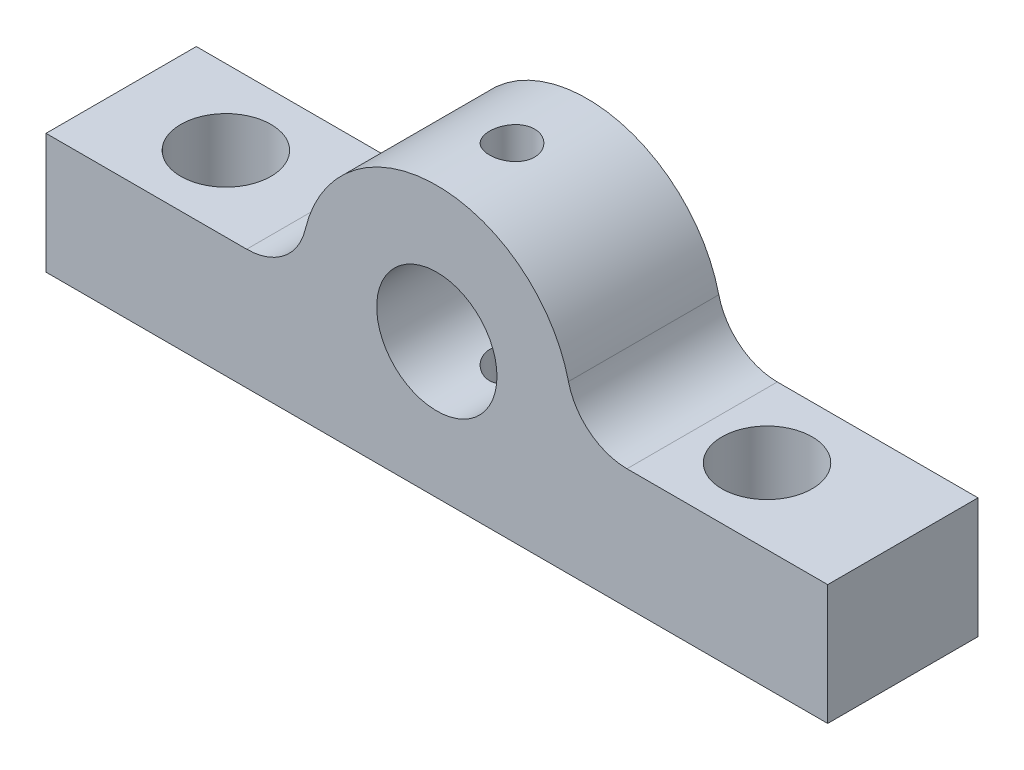
SolidWorks part; units mm, degrees
ref_plane "Front Plane" through (0, 0, 0) normal (0, 0, 1) x (1, 0, 0)
ref_plane "Top Plane" through (0, 0, 0) normal (0, 1, 0) x (1, 0, 0)
ref_plane "Right Plane" through (0, 0, 0) normal (1, 0, 0) x (0, 0, -1)
sketch "Sketch1" plane through (0, 0, 0) normal (0, 0, 1) x (1, 0, 0)
  line L0 (0, -36.257) -> (0, 59.0013) construction
  line L1 (13, 0) -> (-13, 0)
  line L2 (-13, 0) -> (-13, 4)
  line L3 (-13, 4) -> (-6.3246, 4)
  line L4 (13, 4) -> (13, 0)
  line L5 (0, 0) -> (0, 4.5)
  line L6 (6.3246, 4) -> (13, 4)
  arc A0 (4.3785, 5.5385) -> (-4.3785, 5.5385) centre (0, 4.5) ccw
  circle A1 centre (0, 4.5) radius 2
  arc A2 (-4.3785, 5.5385) -> (-6.3246, 4) centre (-6.3246, 6) cw
  arc A3 (6.3246, 4) -> (4.3785, 5.5385) centre (6.3246, 6) cw
  point P6 (0, 0)
  point P17 (4.4721, 4)
  dimension "D1" = 2
  dimension "D2" = 2
extrude "Boss-Extrude1" add sketch "Sketch1" along normal blind 5 contours A1 L0 A0 A2 L3 L2 L1 L5 | L0 A1 L5 L1 L4 L6 A3 A0
sketch "Sketch2" plane through (0, 4, 0) normal (0, 1, 0) x (1, 0, 0)
  line L0 (-0.5173, -2.5) -> (-9.5173, -2.5)
  line L1 (-0.5173, -2.5) -> (8.4827, -2.5)
  circle A0 centre (-9.5173, -2.5) radius 1.5
  circle A1 centre (8.4827, -2.5) radius 1.5
  point P3 (5.2097, -2.5)
  point P4 (4.684, -2.5)
extrude "Cut-Extrude1" cut sketch "Sketch2" against normal blind 5
sketch "Sketch3" plane through (0, 4, 0) normal (0, 1, 0) x (1, 0, 0)
  circle A0 centre (0, -2.5) radius 0.75
extrude "Cut-Extrude2" cut sketch "Sketch3" along normal through all both and the other way through all
